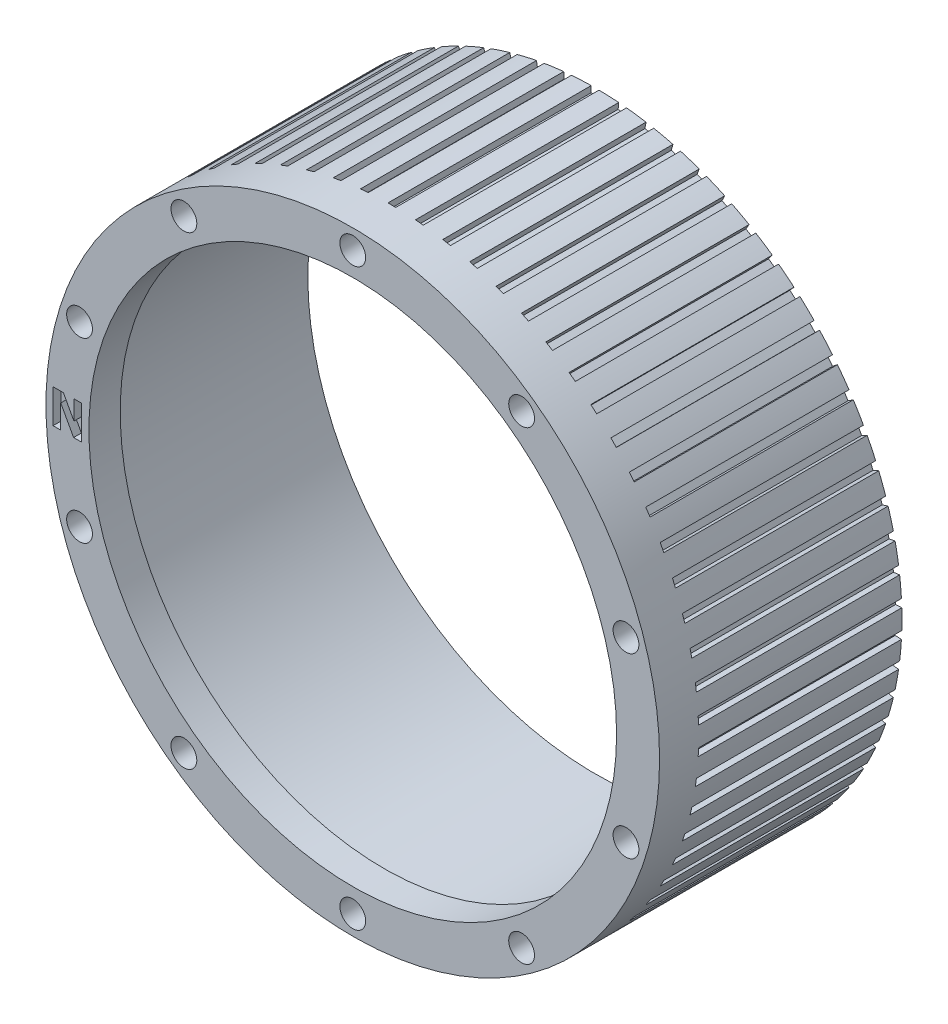
SolidWorks part; units mm, degrees
ref_plane "Front" through (0, 0, 0) normal (0, 0, 1) x (1, 0, 0)
ref_plane "Top" through (0, 0, 0) normal (0, 1, 0) x (1, 0, 0)
ref_plane "Right" through (0, 0, 0) normal (1, 0, 0) x (0, 0, -1)
sketch "Sketch1" plane through (0, 0, 0) normal (0, 0, 1) x (1, 0, 0)
  circle A0 centre (0, 0) radius 36.75 construction
  circle A1 centre (0, 0) radius 39.25
  dimension "D1" = 73.5
  dimension "D2" = 2.5
extrude "Boss-Extrude1" add sketch "Sketch1" along normal blind 31
sketch "Sketch2" plane through (0, 0, 0) normal (0, 0, -1) x (-1, 0, 0)
  circle A0 centre (0, 0) radius 36.75 construction
  circle A1 centre (0, 0) radius 36.75
extrude "Cut-Extrude1" cut sketch "Sketch2" against normal offset from surface (27 mm away) 4 up to face at (39.25, 0, 31)
sketch "Sketch3" plane through (0, 0, 31) normal (0, 0, 1) x (1, 0, 0)
  circle A0 centre (0, 0) radius 36.75 construction
  circle A1 centre (0, 0) radius 36.75 construction
  circle A2 centre (0, 0) radius 33.75
  dimension "D1" = 3
extrude "Cut-Extrude2" cut sketch "Sketch3" against normal up to surface (4 mm away) up to face at (36.75, 0, 27)
sketch "Sketch4" plane through (0, 0, 31) normal (0, 0, 1) x (1, 0, 0)
  line L0 (0, 0) -> (0, 39.25) construction
  circle A0 centre (0, 0) radius 36.75 construction
  circle A1 centre (0, 0) radius 36.75 construction
  circle A2 centre (-34.9513, -11.3564) radius 1.65
  circle A3 centre (0, 0) radius 36.75 construction
  circle A4 centre (-34.9513, 11.3564) radius 1.65
  circle A5 centre (0, 0) radius 36.75 construction
  circle A6 centre (-21.6011, 29.7314) radius 1.65
  circle A7 centre (0, 0) radius 36.75 construction
  circle A8 centre (0, 36.75) radius 1.65
  circle A9 centre (0, 0) radius 36.75 construction
  circle A10 centre (21.6011, 29.7314) radius 1.65
  circle A11 centre (0, 0) radius 36.75 construction
  circle A12 centre (34.9513, 11.3564) radius 1.65
  circle A13 centre (0, 0) radius 36.75 construction
  circle A14 centre (34.9513, -11.3564) radius 1.65
  circle A15 centre (0, 0) radius 36.75 construction
  circle A16 centre (21.6011, -29.7314) radius 1.65
  circle A17 centre (0, 0) radius 36.75 construction
  circle A18 centre (0, -36.75) radius 1.65
  circle A19 centre (0, 0) radius 36.75 construction
  circle A20 centre (-21.6011, -29.7314) radius 1.65
  circle A21 centre (0, 0) radius 39.25 construction
  dimension "D1" = 3.3
  dimension "D3" = 21.6011
  dimension "D2" = 10
extrude "Cut-Extrude3" cut sketch "Sketch4" against normal blind 3
sketch "Sketch5" plane through (0, 0, 0) normal (0, 0, -1) x (-1, 0, 0)
  line L0 (0, 0) -> (0, 39.25) construction
  line L1 (-0.5, 39.25) -> (0.5, 39.25)
  line L2 (-0.5, 39.25) -> (-0.5, 38.45)
  line L3 (-0.5, 38.45) -> (0.5, 38.45)
  line L4 (0.5, 39.25) -> (0.5, 38.45)
  line L5 (-0.5, 39.25) -> (0.5, 38.45) construction
  line L6 (-0.5, 38.45) -> (0.5, 39.25) construction
  line L7 (3.0204, 39.1368) -> (2.9486, 38.34)
  line L8 (3.0204, 39.1368) -> (4.0163, 39.0472)
  line L9 (4.0163, 39.0472) -> (3.9446, 38.2504)
  line L10 (2.9486, 38.34) -> (3.9446, 38.2504)
  line L11 (6.5164, 38.7085) -> (6.3735, 37.9214)
  line L12 (6.5164, 38.7085) -> (7.5003, 38.53)
  line L13 (7.5003, 38.53) -> (7.3575, 37.7428)
  line L14 (6.3735, 37.9214) -> (7.3575, 37.7428)
  line L15 (9.96, 37.9686) -> (9.7471, 37.1974)
  line L16 (9.96, 37.9686) -> (10.9239, 37.7025)
  line L17 (10.9239, 37.7025) -> (10.7111, 36.9314)
  line L18 (9.7471, 37.1974) -> (10.7111, 36.9314)
  line L19 (13.3233, 36.9229) -> (13.0422, 36.1739)
  line L20 (13.3233, 36.9229) -> (14.2596, 36.5715)
  line L21 (14.2596, 36.5715) -> (13.9785, 35.8225)
  line L22 (13.0422, 36.1739) -> (13.9785, 35.8225)
  line L23 (16.5795, 35.58) -> (16.2323, 34.8592)
  line L24 (16.5795, 35.58) -> (17.4804, 35.1461)
  line L25 (17.4804, 35.1461) -> (17.1333, 34.4253)
  line L26 (16.2323, 34.8592) -> (17.1333, 34.4253)
  line L27 (19.7021, 33.9506) -> (19.2918, 33.2638)
  line L28 (19.7021, 33.9506) -> (20.5605, 33.4377)
  line L29 (20.5605, 33.4377) -> (20.1502, 32.7509)
  line L30 (19.2918, 33.2638) -> (20.1502, 32.7509)
  line L31 (22.6661, 32.0478) -> (22.1958, 31.4006)
  line L32 (22.6661, 32.0478) -> (23.4751, 31.46)
  line L33 (23.4751, 31.46) -> (23.0049, 30.8128)
  line L34 (22.1958, 31.4006) -> (23.0049, 30.8128)
  line L35 (25.4476, 29.887) -> (24.9212, 29.2846)
  line L36 (25.4476, 29.887) -> (26.2006, 29.2291)
  line L37 (26.2006, 29.2291) -> (25.6743, 28.6266)
  line L38 (24.9212, 29.2846) -> (25.6743, 28.6266)
  line L39 (28.0242, 27.4856) -> (27.4459, 26.9328)
  line L40 (28.0242, 27.4856) -> (28.7152, 26.7628)
  line L41 (28.7152, 26.7628) -> (28.137, 26.21)
  line L42 (27.4459, 26.9328) -> (28.137, 26.21)
  line L43 (30.3751, 24.8629) -> (29.7497, 24.3641)
  line L44 (30.3751, 24.8629) -> (30.9986, 24.0811)
  line L45 (30.9986, 24.0811) -> (30.3732, 23.5823)
  line L46 (29.7497, 24.3641) -> (30.3732, 23.5823)
  line L47 (32.4816, 22.04) -> (31.8139, 21.5993)
  line L48 (32.4816, 22.04) -> (33.0324, 21.2054)
  line L49 (33.0324, 21.2054) -> (32.3648, 20.7647)
  line L50 (31.8139, 21.5993) -> (32.3648, 20.7647)
  line L51 (34.3264, 19.0396) -> (33.622, 18.6605)
  line L52 (34.3264, 19.0396) -> (34.8003, 18.159)
  line L53 (34.8003, 18.159) -> (34.0958, 17.78)
  line L54 (33.622, 18.6605) -> (34.0958, 17.78)
  line L55 (35.895, 15.886) -> (35.1593, 15.5716)
  line L56 (35.895, 15.886) -> (36.288, 14.9665)
  line L57 (36.288, 14.9665) -> (35.5524, 14.652)
  line L58 (35.1593, 15.5716) -> (35.5524, 14.652)
  line L59 (37.1745, 12.6044) -> (36.4136, 12.3572)
  line L60 (37.1745, 12.6044) -> (37.4835, 11.6534)
  line L61 (37.4835, 11.6534) -> (36.7226, 11.4062)
  line L62 (36.4136, 12.3572) -> (36.7226, 11.4062)
  line L63 (38.1547, 9.2214) -> (37.3747, 9.0434)
  line L64 (38.1547, 9.2214) -> (38.3772, 8.2465)
  line L65 (38.3772, 8.2465) -> (37.5972, 8.0685)
  line L66 (37.3747, 9.0434) -> (37.5972, 8.0685)
  line L67 (38.8277, 5.7641) -> (38.0349, 5.6567)
  line L68 (38.8277, 5.7641) -> (38.9619, 4.7732)
  line L69 (38.9619, 4.7732) -> (38.1691, 4.6658)
  line L70 (38.0349, 5.6567) -> (38.1691, 4.6658)
  line L71 (39.188, 2.2604) -> (38.3889, 2.2245)
  line L72 (39.188, 2.2604) -> (39.2329, 1.2614)
  line L73 (39.2329, 1.2614) -> (38.4337, 1.2256)
  line L74 (38.3889, 2.2245) -> (38.4337, 1.2256)
  line L75 (39.2329, -1.2614) -> (38.4337, -1.2256)
  line L76 (39.2329, -1.2614) -> (39.188, -2.2604)
  line L77 (39.188, -2.2604) -> (38.3889, -2.2245)
  line L78 (38.4337, -1.2256) -> (38.3889, -2.2245)
  line L79 (38.9619, -4.7732) -> (38.1691, -4.6658)
  line L80 (38.9619, -4.7732) -> (38.8277, -5.7641)
  line L81 (38.8277, -5.7641) -> (38.0349, -5.6567)
  line L82 (38.1691, -4.6658) -> (38.0349, -5.6567)
  line L83 (38.3772, -8.2465) -> (37.5972, -8.0685)
  line L84 (38.3772, -8.2465) -> (38.1547, -9.2214)
  line L85 (38.1547, -9.2214) -> (37.3747, -9.0434)
  line L86 (37.5972, -8.0685) -> (37.3747, -9.0434)
  line L87 (37.4835, -11.6534) -> (36.7226, -11.4062)
  line L88 (37.4835, -11.6534) -> (37.1745, -12.6044)
  line L89 (37.1745, -12.6044) -> (36.4136, -12.3572)
  line L90 (36.7226, -11.4062) -> (36.4136, -12.3572)
  line L91 (36.288, -14.9665) -> (35.5524, -14.652)
  line L92 (36.288, -14.9665) -> (35.895, -15.886)
  line L93 (35.895, -15.886) -> (35.1593, -15.5716)
  line L94 (35.5524, -14.652) -> (35.1593, -15.5716)
  line L95 (34.8003, -18.159) -> (34.0958, -17.78)
  line L96 (34.8003, -18.159) -> (34.3264, -19.0396)
  line L97 (34.3264, -19.0396) -> (33.622, -18.6605)
  line L98 (34.0958, -17.78) -> (33.622, -18.6605)
  line L99 (33.0324, -21.2054) -> (32.3648, -20.7647)
  line L100 (33.0324, -21.2054) -> (32.4816, -22.04)
  line L101 (32.4816, -22.04) -> (31.8139, -21.5993)
  line L102 (32.3648, -20.7647) -> (31.8139, -21.5993)
  line L103 (30.9986, -24.0811) -> (30.3732, -23.5823)
  line L104 (30.9986, -24.0811) -> (30.3751, -24.8629)
  line L105 (30.3751, -24.8629) -> (29.7497, -24.3641)
  line L106 (30.3732, -23.5823) -> (29.7497, -24.3641)
  line L107 (28.7152, -26.7628) -> (28.137, -26.21)
  line L108 (28.7152, -26.7628) -> (28.0242, -27.4856)
  line L109 (28.0242, -27.4856) -> (27.4459, -26.9328)
  line L110 (28.137, -26.21) -> (27.4459, -26.9328)
  line L111 (26.2006, -29.2291) -> (25.6743, -28.6266)
  line L112 (26.2006, -29.2291) -> (25.4476, -29.887)
  line L113 (25.4476, -29.887) -> (24.9212, -29.2846)
  line L114 (25.6743, -28.6266) -> (24.9212, -29.2846)
  line L115 (23.4751, -31.46) -> (23.0049, -30.8128)
  line L116 (23.4751, -31.46) -> (22.6661, -32.0478)
  line L117 (22.6661, -32.0478) -> (22.1958, -31.4006)
  line L118 (23.0049, -30.8128) -> (22.1958, -31.4006)
  line L119 (20.5605, -33.4377) -> (20.1502, -32.7509)
  line L120 (20.5605, -33.4377) -> (19.7021, -33.9506)
  line L121 (19.7021, -33.9506) -> (19.2918, -33.2638)
  line L122 (20.1502, -32.7509) -> (19.2918, -33.2638)
  line L123 (17.4804, -35.1461) -> (17.1333, -34.4253)
  line L124 (17.4804, -35.1461) -> (16.5795, -35.58)
  line L125 (16.5795, -35.58) -> (16.2323, -34.8592)
  line L126 (17.1333, -34.4253) -> (16.2323, -34.8592)
  line L127 (14.2596, -36.5715) -> (13.9785, -35.8225)
  line L128 (14.2596, -36.5715) -> (13.3233, -36.9229)
  line L129 (13.3233, -36.9229) -> (13.0422, -36.1739)
  line L130 (13.9785, -35.8225) -> (13.0422, -36.1739)
  line L131 (10.9239, -37.7025) -> (10.7111, -36.9314)
  line L132 (10.9239, -37.7025) -> (9.96, -37.9686)
  line L133 (9.96, -37.9686) -> (9.7471, -37.1974)
  line L134 (10.7111, -36.9314) -> (9.7471, -37.1974)
  line L135 (7.5003, -38.53) -> (7.3575, -37.7428)
  line L136 (7.5003, -38.53) -> (6.5164, -38.7085)
  line L137 (6.5164, -38.7085) -> (6.3735, -37.9214)
  line L138 (7.3575, -37.7428) -> (6.3735, -37.9214)
  line L139 (4.0163, -39.0472) -> (3.9446, -38.2504)
  line L140 (4.0163, -39.0472) -> (3.0204, -39.1368)
  line L141 (3.0204, -39.1368) -> (2.9486, -38.34)
  line L142 (3.9446, -38.2504) -> (2.9486, -38.34)
  line L143 (0.5, -39.25) -> (0.5, -38.45)
  line L144 (0.5, -39.25) -> (-0.5, -39.25)
  line L145 (-0.5, -39.25) -> (-0.5, -38.45)
  line L146 (0.5, -38.45) -> (-0.5, -38.45)
  line L147 (-3.0204, -39.1368) -> (-2.9486, -38.34)
  line L148 (-3.0204, -39.1368) -> (-4.0163, -39.0472)
  line L149 (-4.0163, -39.0472) -> (-3.9446, -38.2504)
  line L150 (-2.9486, -38.34) -> (-3.9446, -38.2504)
  line L151 (-6.5164, -38.7085) -> (-6.3735, -37.9214)
  line L152 (-6.5164, -38.7085) -> (-7.5003, -38.53)
  line L153 (-7.5003, -38.53) -> (-7.3575, -37.7428)
  line L154 (-6.3735, -37.9214) -> (-7.3575, -37.7428)
  line L155 (-9.96, -37.9686) -> (-9.7471, -37.1974)
  line L156 (-9.96, -37.9686) -> (-10.9239, -37.7025)
  line L157 (-10.9239, -37.7025) -> (-10.7111, -36.9314)
  line L158 (-9.7471, -37.1974) -> (-10.7111, -36.9314)
  line L159 (-13.3233, -36.9229) -> (-13.0422, -36.1739)
  line L160 (-13.3233, -36.9229) -> (-14.2596, -36.5715)
  line L161 (-14.2596, -36.5715) -> (-13.9785, -35.8225)
  line L162 (-13.0422, -36.1739) -> (-13.9785, -35.8225)
  line L163 (-16.5795, -35.58) -> (-16.2323, -34.8592)
  line L164 (-16.5795, -35.58) -> (-17.4804, -35.1461)
  line L165 (-17.4804, -35.1461) -> (-17.1333, -34.4253)
  line L166 (-16.2323, -34.8592) -> (-17.1333, -34.4253)
  line L167 (-19.7021, -33.9506) -> (-19.2918, -33.2638)
  line L168 (-19.7021, -33.9506) -> (-20.5605, -33.4377)
  line L169 (-20.5605, -33.4377) -> (-20.1502, -32.7509)
  line L170 (-19.2918, -33.2638) -> (-20.1502, -32.7509)
  line L171 (-22.6661, -32.0478) -> (-22.1958, -31.4006)
  line L172 (-22.6661, -32.0478) -> (-23.4751, -31.46)
  line L173 (-23.4751, -31.46) -> (-23.0049, -30.8128)
  line L174 (-22.1958, -31.4006) -> (-23.0049, -30.8128)
  line L175 (-25.4476, -29.887) -> (-24.9212, -29.2846)
  line L176 (-25.4476, -29.887) -> (-26.2006, -29.2291)
  line L177 (-26.2006, -29.2291) -> (-25.6743, -28.6266)
  line L178 (-24.9212, -29.2846) -> (-25.6743, -28.6266)
  line L179 (-28.0242, -27.4856) -> (-27.4459, -26.9328)
  line L180 (-28.0242, -27.4856) -> (-28.7152, -26.7628)
  line L181 (-28.7152, -26.7628) -> (-28.137, -26.21)
  line L182 (-27.4459, -26.9328) -> (-28.137, -26.21)
  line L183 (-30.3751, -24.8629) -> (-29.7497, -24.3641)
  line L184 (-30.3751, -24.8629) -> (-30.9986, -24.0811)
  line L185 (-30.9986, -24.0811) -> (-30.3732, -23.5823)
  line L186 (-29.7497, -24.3641) -> (-30.3732, -23.5823)
  line L187 (-32.4816, -22.04) -> (-31.8139, -21.5993)
  line L188 (-32.4816, -22.04) -> (-33.0324, -21.2054)
  line L189 (-33.0324, -21.2054) -> (-32.3648, -20.7647)
  line L190 (-31.8139, -21.5993) -> (-32.3648, -20.7647)
  line L191 (-34.3264, -19.0396) -> (-33.622, -18.6605)
  line L192 (-34.3264, -19.0396) -> (-34.8003, -18.159)
  line L193 (-34.8003, -18.159) -> (-34.0958, -17.78)
  line L194 (-33.622, -18.6605) -> (-34.0958, -17.78)
  line L195 (-35.895, -15.886) -> (-35.1593, -15.5716)
  line L196 (-35.895, -15.886) -> (-36.288, -14.9665)
  line L197 (-36.288, -14.9665) -> (-35.5524, -14.652)
  line L198 (-35.1593, -15.5716) -> (-35.5524, -14.652)
  line L199 (-37.1745, -12.6044) -> (-36.4136, -12.3572)
  line L200 (-37.1745, -12.6044) -> (-37.4835, -11.6534)
  line L201 (-37.4835, -11.6534) -> (-36.7226, -11.4062)
  line L202 (-36.4136, -12.3572) -> (-36.7226, -11.4062)
  line L203 (-38.1547, -9.2214) -> (-37.3747, -9.0434)
  line L204 (-38.1547, -9.2214) -> (-38.3772, -8.2465)
  line L205 (-38.3772, -8.2465) -> (-37.5972, -8.0685)
  line L206 (-37.3747, -9.0434) -> (-37.5972, -8.0685)
  line L207 (-38.8277, -5.7641) -> (-38.0349, -5.6567)
  line L208 (-38.8277, -5.7641) -> (-38.9619, -4.7732)
  line L209 (-38.9619, -4.7732) -> (-38.1691, -4.6658)
  line L210 (-38.0349, -5.6567) -> (-38.1691, -4.6658)
  line L211 (-39.188, -2.2604) -> (-38.3889, -2.2245)
  line L212 (-39.188, -2.2604) -> (-39.2329, -1.2614)
  line L213 (-39.2329, -1.2614) -> (-38.4337, -1.2256)
  line L214 (-38.3889, -2.2245) -> (-38.4337, -1.2256)
  line L215 (-39.2329, 1.2614) -> (-38.4337, 1.2256)
  line L216 (-39.2329, 1.2614) -> (-39.188, 2.2604)
  line L217 (-39.188, 2.2604) -> (-38.3889, 2.2245)
  line L218 (-38.4337, 1.2256) -> (-38.3889, 2.2245)
  line L219 (-38.9619, 4.7732) -> (-38.1691, 4.6658)
  line L220 (-38.9619, 4.7732) -> (-38.8277, 5.7641)
  line L221 (-38.8277, 5.7641) -> (-38.0349, 5.6567)
  line L222 (-38.1691, 4.6658) -> (-38.0349, 5.6567)
  line L223 (-38.3772, 8.2465) -> (-37.5972, 8.0685)
  line L224 (-38.3772, 8.2465) -> (-38.1547, 9.2214)
  line L225 (-38.1547, 9.2214) -> (-37.3747, 9.0434)
  line L226 (-37.5972, 8.0685) -> (-37.3747, 9.0434)
  line L227 (-37.4835, 11.6534) -> (-36.7226, 11.4062)
  line L228 (-37.4835, 11.6534) -> (-37.1745, 12.6044)
  line L229 (-37.1745, 12.6044) -> (-36.4136, 12.3572)
  line L230 (-36.7226, 11.4062) -> (-36.4136, 12.3572)
  line L231 (-36.288, 14.9665) -> (-35.5524, 14.652)
  line L232 (-36.288, 14.9665) -> (-35.895, 15.886)
  line L233 (-35.895, 15.886) -> (-35.1593, 15.5716)
  line L234 (-35.5524, 14.652) -> (-35.1593, 15.5716)
  line L235 (-34.8003, 18.159) -> (-34.0958, 17.78)
  line L236 (-34.8003, 18.159) -> (-34.3264, 19.0396)
  line L237 (-34.3264, 19.0396) -> (-33.622, 18.6605)
  line L238 (-34.0958, 17.78) -> (-33.622, 18.6605)
  line L239 (-33.0324, 21.2054) -> (-32.3648, 20.7647)
  line L240 (-33.0324, 21.2054) -> (-32.4816, 22.04)
  line L241 (-32.4816, 22.04) -> (-31.8139, 21.5993)
  line L242 (-32.3648, 20.7647) -> (-31.8139, 21.5993)
  line L243 (-30.9986, 24.0811) -> (-30.3732, 23.5823)
  line L244 (-30.9986, 24.0811) -> (-30.3751, 24.8629)
  line L245 (-30.3751, 24.8629) -> (-29.7497, 24.3641)
  line L246 (-30.3732, 23.5823) -> (-29.7497, 24.3641)
  line L247 (-28.7152, 26.7628) -> (-28.137, 26.21)
  line L248 (-28.7152, 26.7628) -> (-28.0242, 27.4856)
  line L249 (-28.0242, 27.4856) -> (-27.4459, 26.9328)
  line L250 (-28.137, 26.21) -> (-27.4459, 26.9328)
  line L251 (-26.2006, 29.2291) -> (-25.6743, 28.6266)
  line L252 (-26.2006, 29.2291) -> (-25.4476, 29.887)
  line L253 (-25.4476, 29.887) -> (-24.9212, 29.2846)
  line L254 (-25.6743, 28.6266) -> (-24.9212, 29.2846)
  line L255 (-23.4751, 31.46) -> (-23.0049, 30.8128)
  line L256 (-23.4751, 31.46) -> (-22.6661, 32.0478)
  line L257 (-22.6661, 32.0478) -> (-22.1958, 31.4006)
  line L258 (-23.0049, 30.8128) -> (-22.1958, 31.4006)
  line L259 (-20.5605, 33.4377) -> (-20.1502, 32.7509)
  line L260 (-20.5605, 33.4377) -> (-19.7021, 33.9506)
  line L261 (-19.7021, 33.9506) -> (-19.2918, 33.2638)
  line L262 (-20.1502, 32.7509) -> (-19.2918, 33.2638)
  line L263 (-17.4804, 35.1461) -> (-17.1333, 34.4253)
  line L264 (-17.4804, 35.1461) -> (-16.5795, 35.58)
  line L265 (-16.5795, 35.58) -> (-16.2323, 34.8592)
  line L266 (-17.1333, 34.4253) -> (-16.2323, 34.8592)
  line L267 (-14.2596, 36.5715) -> (-13.9785, 35.8225)
  line L268 (-14.2596, 36.5715) -> (-13.3233, 36.9229)
  line L269 (-13.3233, 36.9229) -> (-13.0422, 36.1739)
  line L270 (-13.9785, 35.8225) -> (-13.0422, 36.1739)
  line L271 (-10.9239, 37.7025) -> (-10.7111, 36.9314)
  line L272 (-10.9239, 37.7025) -> (-9.96, 37.9686)
  line L273 (-9.96, 37.9686) -> (-9.7471, 37.1974)
  line L274 (-10.7111, 36.9314) -> (-9.7471, 37.1974)
  line L275 (-7.5003, 38.53) -> (-7.3575, 37.7428)
  line L276 (-7.5003, 38.53) -> (-6.5164, 38.7085)
  line L277 (-6.5164, 38.7085) -> (-6.3735, 37.9214)
  line L278 (-7.3575, 37.7428) -> (-6.3735, 37.9214)
  line L279 (-4.0163, 39.0472) -> (-3.9446, 38.2504)
  line L280 (-4.0163, 39.0472) -> (-3.0204, 39.1368)
  line L281 (-3.0204, 39.1368) -> (-2.9486, 38.34)
  line L282 (-3.9446, 38.2504) -> (-2.9486, 38.34)
  circle A1 centre (0, 0) radius 39.25 construction
  point P0 (0, 38.85)
  point P10 (0, 39.25)
  dimension "D1" = 0.8
  dimension "D2" = 1
  dimension "D3" = 70
extrude "Cut-Extrude4" cut sketch "Sketch5" against normal offset from surface (26 mm away) 5 up to face at (1.65, -36.75, 31)
sketch "Sketch6" plane through (0, 0, 31) normal (0, 0, 1) x (1, 0, 0)
  text T0 "N" font "Tahoma" height in points 16
extrude "Cut-Extrude5" cut sketch "Sketch6" against normal blind 1
